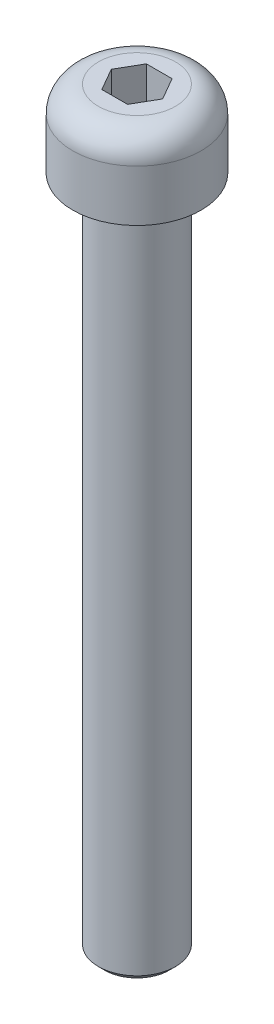
SolidWorks part; units mm, degrees
material "Cast Carbon Steel"
ref_plane "Front Plane" through (0, 0, 0) normal (0, 0, 1) x (1, 0, 0)
ref_plane "Top Plane" through (0, 0, 0) normal (0, 1, 0) x (1, 0, 0)
ref_plane "Right Plane" through (0, 0, 0) normal (1, 0, 0) x (0, 0, -1)
sketch "Sketch1" plane through (0, 0, 0) normal (0, 1, 0) x (1, 0, 0)
  circle A0 centre (0, 0) radius 1.5
  dimension "D1" = 3
extrude "Boss-Extrude1" add sketch "Sketch1" along normal blind 26.25
sketch "Sketch2" plane through (0, 26.25, 0) normal (0, 1, 0) x (1, 0, 0)
  circle A0 centre (0, 0) radius 2.5
  dimension "D1" = 5
extrude "Boss-Extrude2" add sketch "Sketch2" along normal blind 3
fillet "Fillet1" radius 1 1 edges at (0, 29.25, 2.5)
chamfer "Chamfer1" distance 0.25 angle 45 1 edges at (0, 0, 1.5)
sketch "Sketch3" plane through (0, 29.25, 0) normal (0, 1, 0) x (1, 0, 0)
  line L1 (-1, 0) -> (-0.5, -0.866)
  line L2 (-0.5, -0.866) -> (0.5, -0.866)
  line L3 (0.5, -0.866) -> (1, 0)
  line L4 (1, 0) -> (0.5, 0.866)
  line L5 (0.5, 0.866) -> (-0.5, 0.866)
  line L6 (-0.5, 0.866) -> (-1, 0)
  circle A0 centre (0, 0) radius 0.866 construction
  dimension "D1" = 1
extrude "Cut-Extrude1" cut sketch "Sketch3" against normal blind 2
